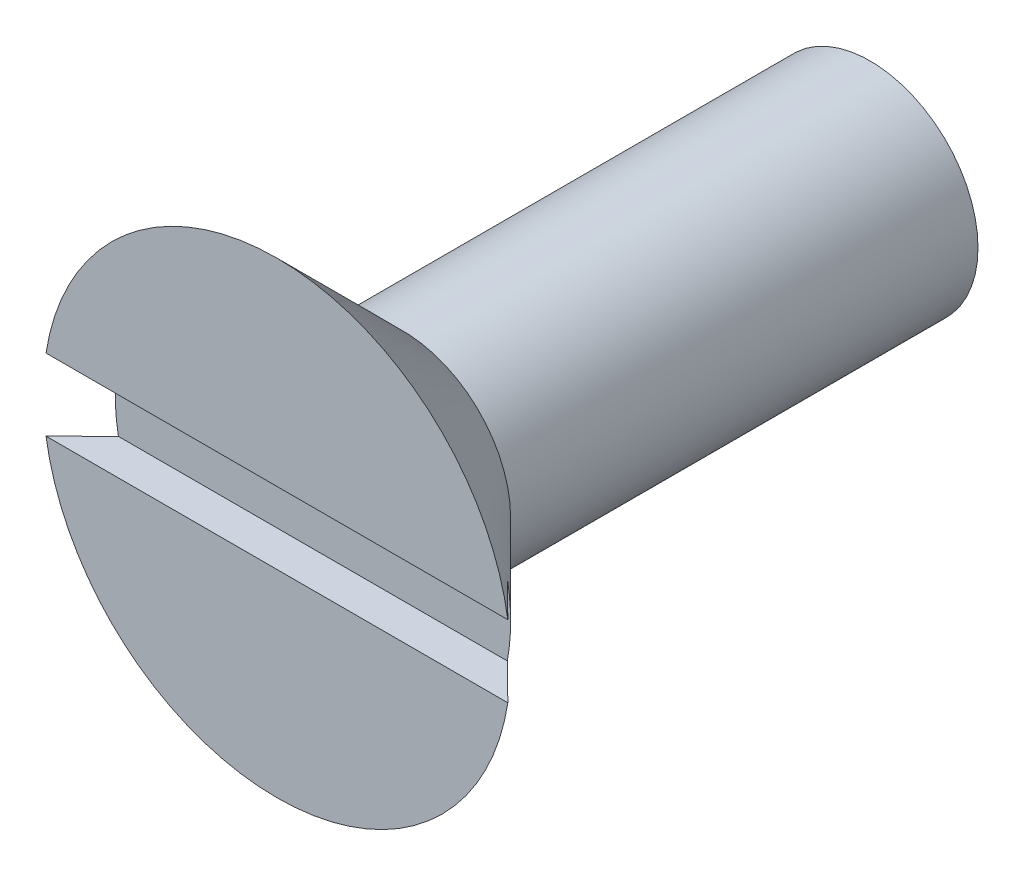
SolidWorks part; units mm, degrees
material "Alloy Steel"
ref_plane "Front Plane" through (0, 0, 0) normal (0, 0, 1) x (1, 0, 0)
ref_plane "Top Plane" through (0, 0, 0) normal (0, 1, 0) x (1, 0, 0)
ref_plane "Right Plane" through (0, 0, 0) normal (1, 0, 0) x (0, 0, -1)
sketch "Sketch1" plane through (0, 0, 0) normal (1, 0, 0) x (0, 0, -1)
  line L0 (-15.2494, 0) -> (15.2494, 0) construction
  line L1 (10.1929, 0) -> (8.4609, 3)
  line L2 (8.4609, 3) -> (-4.5391, 3)
  line L3 (-4.5391, 3) -> (-8.0391, 6.5)
  line L4 (-8.0391, 6.5) -> (-8.0391, 0)
  line L5 (10.1929, 0) -> (-8.0391, 0)
  point P4 (0, 0)
  dimension "D1" = 13
  dimension "D2" = 60
  dimension "D3" = 6
  dimension "D4" = 45
  dimension "D5" = 6.5
  dimension "D6" = 8.4609
revolve "Revolve1" add sketch "Sketch1" angle 360 about L0
sketch "Sketch2" plane through (0, 0, 0) normal (1, 0, 0) x (0, 0, -1)
  line L0 (-8.0391, 6.5) -> (-8.0391, -6.5) construction
  line L1 (-9.0391, 1) -> (-7.0391, 1)
  line L2 (-9.0391, 1) -> (-9.0391, -1)
  line L3 (-9.0391, -1) -> (-7.0391, -1)
  line L4 (-7.0391, 1) -> (-7.0391, -1)
  line L5 (-8.0391, -1) -> (-8.0391, 1) construction
  line L6 (-9.0391, 0) -> (-7.0391, 0) construction
  point P0 (-8.0391, 0)
  dimension "D1" = 2
  dimension "D2" = 1
extrude "Cut-Extrude1" cut sketch "Sketch2" against normal through all and the other way through all
